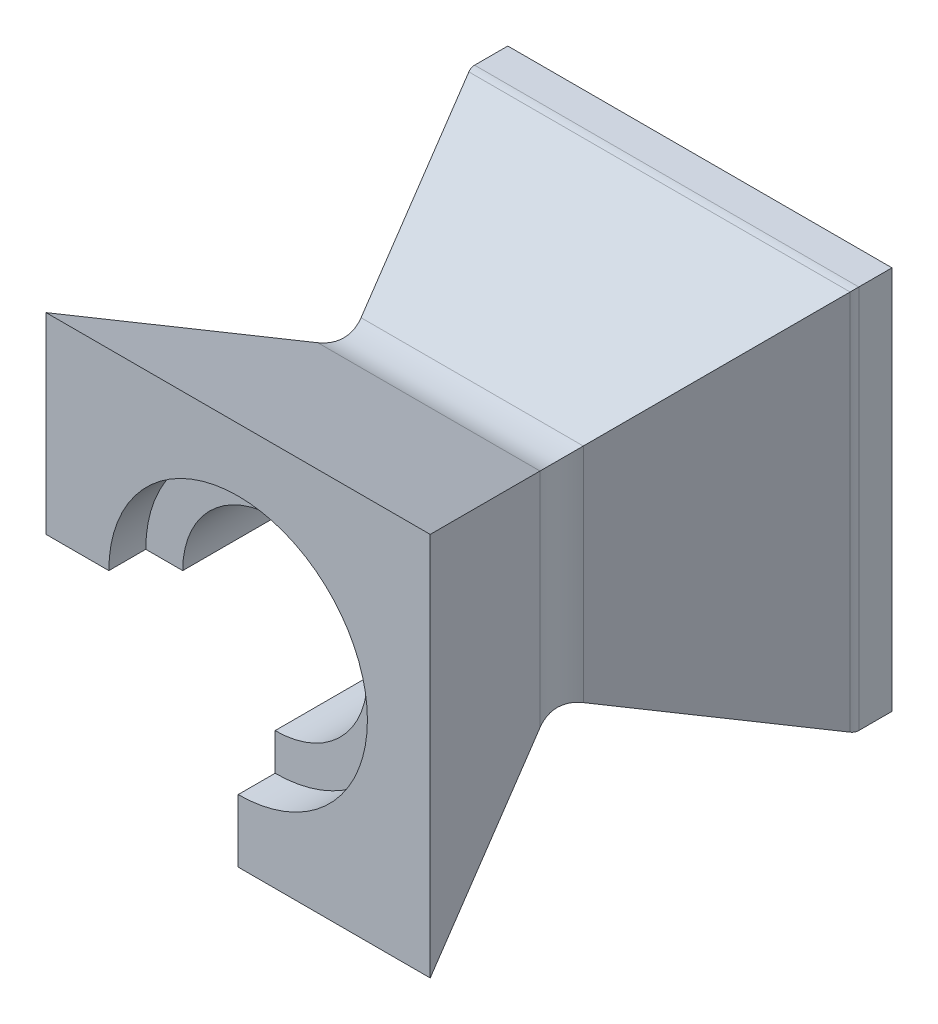
SolidWorks part; units mm, degrees
material "Cast Stainless Steel"
ref_plane "Front Plane" through (0, 0, 0) normal (0, 0, 1) x (1, 0, 0)
ref_plane "Top Plane" through (0, 0, 0) normal (0, 1, 0) x (1, 0, 0)
ref_plane "Right Plane" through (0, 0, 0) normal (1, 0, 0) x (0, 0, -1)
sketch "Sketch4" plane through (0, 0, 0) normal (0, 0, 1) x (1, 0, 0)
  line L0 (104, 104) -> (0, 0) construction
  line L1 (0, 0) -> (104, 0)
  line L2 (0, 0) -> (0, 104)
  line L3 (0, 104) -> (104, 104)
  line L4 (104, 0) -> (104, 104)
  line L5 (0, 104) -> (104, 0) construction
  dimension "D1" = 104
  dimension "D2" = 104
extrude "Boss-Extrude2" add sketch "Sketch4" along normal blind 57.5 draft 23
mirror "Mirror2" about plane through (0, 0, 57.5) normal (0, 0, -1) of "Boss-Extrude2"
sketch "Sketch6" plane through (0, 0, 115) normal (0, 0, 1) x (1, 0, 0)
  line L0 (104, 0) -> (104, 104) construction
  line L1 (104, 104) -> (0, 104) construction
  circle A0 centre (52, 52) radius 25
  dimension "D1" = 50
  dimension "D2" = 52
  dimension "D3" = 52
extrude "Cut-Extrude1" cut sketch "Sketch6" against normal blind 179.5
sketch "Sketch8" plane through (0, 0, 0) normal (0, 0, 1) x (1, 0, 0)
  line L0 (52, 0) -> (52, 104) construction
  line L1 (0, 52) -> (104, 52) construction
  line L2 (0, 104) -> (0, 0) construction
  arc A0 (52, 17) -> (17, 52) centre (52, 52) ccw
  arc A1 (52, 27) -> (27, 52) centre (52, 52) ccw
  point P6 (52, 52)
  point P9 (52, 52)
  dimension "D1" = 70
  dimension "D2" = 50
extrude "Cut-Extrude-Thin1" cut sketch "Sketch8" along normal blind 10 thin
sketch "Sketch9" plane through (0, 0, 0) normal (0, 0, -1) x (-1, 0, 0)
  line L0 (-27, 52) -> (0, 52)
  line L1 (0, 104) -> (0, 0) construction
  line L2 (0, 52) -> (0, 0)
  line L3 (0, 0) -> (-52, 0)
  line L4 (0, 0) -> (-104, 0) construction
  line L5 (-52, 0) -> (-52, 27)
  line L6 (-52, 27) -> (-52, 52)
  line L7 (-52, 52) -> (-27, 52)
extrude "Cut-Extrude3" cut sketch "Sketch9" against normal blind 124
sketch "Sketch10" plane through (0, 0, 115) normal (0, 0, 1) x (1, 0, 0)
  circle A0 centre (52, 52) radius 35
  dimension "D1" = 70
extrude "Cut-Extrude4" cut sketch "Sketch10" against normal blind 10
fillet "Fillet9" radius 15 1 edges at (65.7963, 24.4073, 57.5)
fillet "Fillet10" radius 15 3 edges at (24.4073, 65.7963, 57.5) (52, 79.5927, 57.5) (79.5927, 51.3523, 57.5)
sketch "Sketch12" plane through (0, 0, 0) normal (0, 0, -1) x (-1, 0, 0)
  line L1 (-104, 104) -> (0, 104)
  line L2 (-104, 104) -> (-104, 0)
  line L4 (0, 104) -> (0, 52)
  line L5 (-101, 101) -> (-3, 101)
  line L6 (-101, 101) -> (-101, 3)
  line L8 (-3, 101) -> (-3, 52)
  line L9 (-3, 52) -> (0, 52)
  line L10 (-52, 0) -> (-104, 0) construction
  line L11 (-104, 0) -> (-52, 0)
  line L12 (-101, 3) -> (-52, 3)
  line L13 (-52, 7) -> (-52, 0) construction
  line L14 (-52, 3) -> (-52, 0)
  point P13 (-52, 0)
  dimension "D1" = 3
  dimension "D2" = 3
  dimension "D3" = 3
  dimension "D4" = 3
  dimension "D5" = 52
  dimension "D8" = 3
extrude "Boss-Extrude5" add sketch "Sketch12" along normal blind 10
fillet "Fillet16" radius 5 1 edges at (78, 0, 0)
fillet "Fillet17" radius 5 3 edges at (0, 78, 0) (52, 104, 0) (104, 52.0523, 0)
sketch "Sketch14" plane through (0, 0, 0) normal (0, 0, -1) x (-1, 0, 0)
  line L0 (-96.6066, 96.6066) -> (-86, 86) construction
  line L1 (-94.4853, 98.7279) -> (-83.8787, 88.1213)
  line L2 (-98.7279, 94.4853) -> (-88.1213, 83.8787)
  line L3 (-101, 101) -> (-3, 101) construction
  line L9 (-52, 27) -> (-52, 77) construction
  line L10 (-97, 52) -> (-7, 52) construction
  arc A0 (-94.4853, 98.7279) -> (-98.7279, 94.4853) centre (-96.6066, 96.6066) ccw
  arc A1 (-88.1213, 83.8787) -> (-83.8787, 88.1213) centre (-86, 86) ccw
  arc A6 (-27, 52) -> (-52, 27) centre (-52, 52) ccw construction
  arc A7 (-7, 52) -> (-52, 7) centre (-52, 52) ccw construction
  point P2 (-91.3033, 91.3033)
  point P28 (-52, 52)
  point P32 (-52, 52)
  dimension "D1" = 3
  dimension "D3" = 3
  dimension "D5" = 34
  dimension "D2" = 15
  dimension "D4" = 45
extrude "Cut-Extrude6" cut sketch "Sketch14" against normal blind 10
sketch "Sketch15" plane through (0, 0, 0) normal (0, 0, -1) x (-1, 0, 0)
  line L0 (-52, 27) -> (-52, 77) construction
  line L1 (-77, 52) -> (-27, 52) construction
  line L2 (-52, 52) -> (-3, 101) construction
  line L3 (-18.049, 85.951) -> (-7.4424, 96.5576) construction
  line L4 (-20.1703, 88.0723) -> (-9.5637, 98.6789)
  line L5 (-15.9277, 83.8297) -> (-5.3211, 94.4363)
  line L7 (-101, 101) -> (-3, 101) construction
  line L8 (-52, 52) -> (-104, 0) construction
  line L9 (-85.9534, 18.0466) -> (-96.56, 7.44) construction
  line L10 (-83.8321, 15.9253) -> (-94.4387, 5.3187)
  line L11 (-88.0747, 20.1679) -> (-98.6813, 9.5613)
  line L12 (-52, 3) -> (-101, 3) construction
  arc A0 (-27, 52) -> (-52, 27) centre (-52, 52) ccw construction
  arc A1 (-20.1703, 88.0723) -> (-15.9277, 83.8297) centre (-18.049, 85.951) ccw
  arc A2 (-5.3211, 94.4363) -> (-9.5637, 98.6789) centre (-7.4424, 96.5576) ccw
  arc A5 (-83.8321, 15.9253) -> (-88.0747, 20.1679) centre (-85.9534, 18.0466) ccw
  arc A6 (-98.6813, 9.5613) -> (-94.4387, 5.3187) centre (-96.56, 7.44) ccw
  point P8 (-52, 52)
  point P12 (-52, 52)
  point P17 (-12.7457, 91.2543)
  point P24 (-91.2567, 12.7433)
  dimension "D1" = 3
  dimension "D2" = 15
  dimension "D3" = 4.4424
  dimension "D4" = 3
  dimension "D6" = 4.44
  dimension "D5" = 15
extrude "Cut-Extrude7" cut sketch "Sketch15" against normal blind 10
